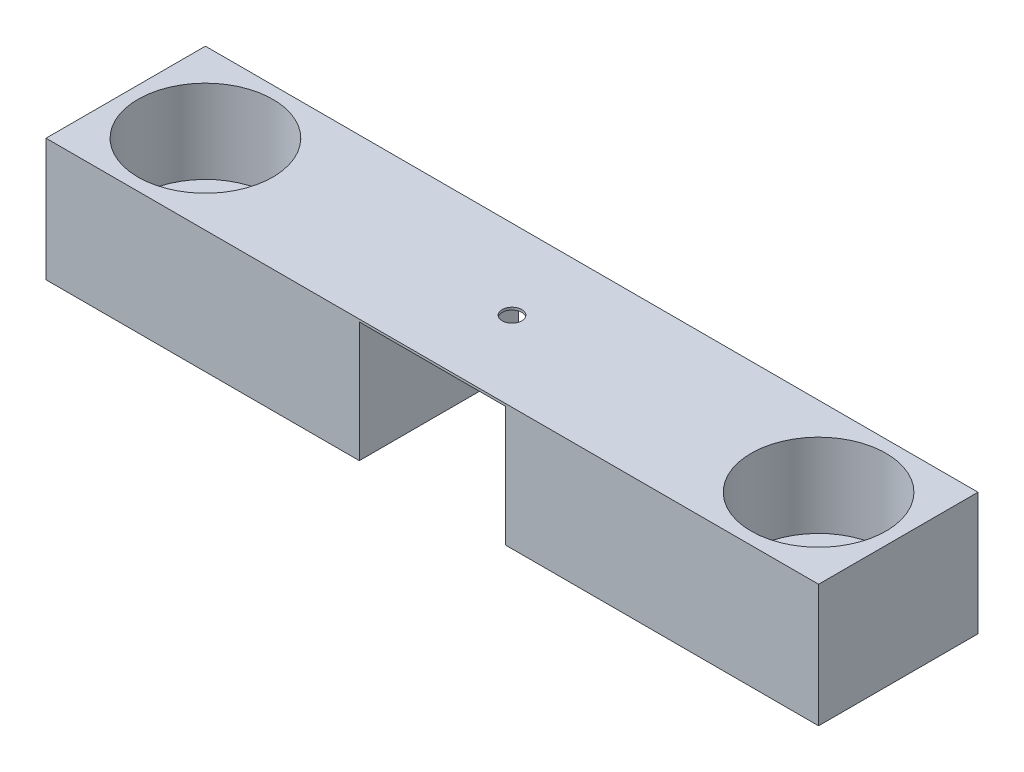
SolidWorks part; units mm, degrees
material "6061 合金"
ref_plane "前视基准面" through (0, 0, 0) normal (0, 0, 1) x (1, 0, 0)
ref_plane "上视基准面" through (0, 0, 0) normal (0, 1, 0) x (1, 0, 0)
ref_plane "右视基准面" through (0, 0, 0) normal (1, 0, 0) x (0, 0, -1)
sketch "草图1" plane through (0, 0, 0) normal (0, 1, 0) x (1, 0, 0)
  line L1 (-31.5, 6.5) -> (31.5, 6.5)
  line L2 (-31.5, 6.5) -> (-31.5, -6.5)
  line L3 (-31.5, -6.5) -> (31.5, -6.5)
  line L4 (31.5, 6.5) -> (31.5, -6.5)
  line L5 (-31.5, 6.5) -> (31.5, -6.5) construction
  line L6 (-31.5, -6.5) -> (31.5, 6.5) construction
  point P0 (0, 0)
extrude "凸台-拉伸1" add sketch "草图1" along normal blind 10
sketch "草图2" plane through (0, 10, 0) normal (0, 1, 0) x (1, 0, 0)
  line L0 (-25, 0) -> (25, 0) construction
  line L1 (-16.5, 0) -> (16.5, 0) construction
  point P6 (0, 0)
hole_wizard "打孔尺寸(%根据)内六角圆柱头螺钉的类型1" positions "3D草图1" profile "草图3" counterbore size "M6" standard "GB" end condition through all
sketch3d "3D草图1"
  point P0 (-25, 10, 0)
  point P3 (25, 10, 0)
sketch "草图3" plane through (-25, 10, 0) normal (1, 0, 0) x (0, 0, 1)
  line L0 (0, 0) -> (0, 10)
  line L1 (0, 10) -> (3.3, 10)
  line L3 (3.3, 10) -> (3.3, 6.8)
  line L4 (3.3, 6.8) -> (5.5, 6.8)
  line L5 (5.5, 6.8) -> (5.5, 0)
  line L7 (5.5, 0) -> (0, 0)
  line L11 (0, -6.35) -> (0, 107.95) construction
  dimension "通孔孔直径" = 6.6
  dimension "通孔孔深度" = 10
  dimension "柱形沉头孔直径" = 11
  dimension "柱形沉头孔深度" = 6.8
sketch "草图4" plane through (0, 0, 0) normal (0, -1, 0) x (1, 0, 0)
  line L0 (-25, 0) -> (-15, 0) construction
  line L1 (-25, 0) -> (25, 0) construction
  line L2 (25, 0) -> (15, 0) construction
  dimension "D1" = 10
  dimension "D2" = 10
hole_wizard "大小mm 暗销孔1" positions "3D草图2" profile "草图5" hole size "Ø4.0" standard "GB"
sketch3d "3D草图2"
  point P0 (-15, 0, 0)
sketch "草图5" plane through (-15, 0, 0) normal (1, 0, 0) x (0, 0, -1)
  line L0 (0, 0) -> (0, 6.2017)
  line L1 (0, 6.2017) -> (2, 5)
  line L2 (2, 5) -> (2, 0)
  line L5 (2, 0) -> (0, 0)
  line L10 (0, 6.2017) -> (-2, 5) construction
  line L11 (0, -6.35) -> (0, 107.95) construction
  dimension "孔直径" = 4
  dimension "孔深度" = 5
  dimension "导头角度" = 118
sketch "草图6" plane through (0, 0, 0) normal (0, -1, 0) x (1, 0, 0)
  line L0 (14.5, 0) -> (15.5, 0) construction
  line L1 (-25, 0) -> (25, 0) construction
  line L2 (14.5, 2) -> (15.5, 2)
  line L3 (14.5, -2) -> (15.5, -2)
  arc A0 (14.5, 2) -> (14.5, -2) centre (14.5, 0) ccw
  arc A1 (15.5, -2) -> (15.5, 2) centre (15.5, 0) ccw
  circle A2 centre (-15, 0) radius 2 construction
  point P5 (15, 0)
  dimension "D1" = 1
extrude "切除-拉伸1" cut sketch "草图6" against normal blind 5
fillet "圆角1" [suppressed] radius 2
sketch "草图7" plane through (0, 10, 0) normal (0, 1, 0) x (1, 0, 0)
  circle A0 centre (0, 0) radius 2
hole_wizard "M2 螺纹孔1" positions "3D草图3" profile "草图8" tap size "M2" standard "GB" end condition through all
sketch3d "3D草图3"
  line L0 (-25, 10, 0) -> (25, 10, 0) construction
  point P0 (0, 10, 0)
  point P4 (0, 10, 0)
  point P6 (0, 10, 0)
cosmetic thread "孔螺蚊线3" parameters "D2"=2
sketch "草图8" plane through (0, 10, 0) normal (1, 0, 0) x (0, 0, 1)
  line L0 (0, 0) -> (0, 10)
  line L1 (0, 10) -> (0.8, 10)
  line L2 (0.8, 10) -> (0.8, 0)
  line L5 (0.8, 0) -> (0, 0)
  line L11 (0, -6.35) -> (0, 107.95) construction
  dimension "通孔螺纹孔钻头直径" = 1.6
  dimension "通孔螺纹孔钻头深度" = 10
cosmetic thread "孔螺蚊线4" parameters "D2"=2
cosmetic thread "孔螺蚊线5" parameters "D2"=2
sketch "草图9" plane through (0, 0, 6.5) normal (0, 0, 1) x (1, 0, 0)
  line L0 (7.15, 0) -> (-7.15, 0) construction
  line L1 (-5.95, 9.8) -> (5.95, 9.8)
  line L2 (-5.95, 9.8) -> (-5.95, 0)
  line L3 (-5.95, 0) -> (5.95, 0)
  line L4 (5.95, 9.8) -> (5.95, 0)
  dimension "D1" = 9.8
  dimension "D2" = 5.95
  dimension "D3" = 11.9
extrude "切除-拉伸2" cut sketch "草图9" against normal through all
sketch "草图10" [suppressed] plane through (0, 0, 0) normal (0, -1, 0) x (-1, 0, 0)
  line L0 (15, 0) -> (15, -4) construction
  line L1 (15, -4) -> (17, -4) construction
  line L2 (-15, 0) -> (-15, 4) construction
  line L3 (-15, 4) -> (-17, 4) construction
  circle A0 centre (17, -4) radius 1.5009
  circle A1 centre (-17, 4) radius 1.5328
  dimension "D1" = 4
  dimension "D2" = 2
hole_wizard "大小mm 暗销孔2" [suppressed] positions "3D草图4" profile "草图11" hole size "Ø4.0" standard "GB"
sketch3d "3D草图4" [suppressed]
  point P0 (-17, 0, 4)
sketch "草图11" plane through (-17, 0, 4) normal (1, 0, 0) x (0, 0, -1)
  line L0 (0, 0) -> (0, 6.2017)
  line L1 (0, 6.2017) -> (2, 5)
  line L2 (2, 5) -> (2, 0)
  line L5 (2, 0) -> (0, 0)
  line L10 (0, 6.2017) -> (-2, 5) construction
  line L11 (0, -6.35) -> (0, 107.95) construction
  dimension "孔直径" = 4
  dimension "孔深度" = 5
  dimension "导头角度" = 118
sketch "草图12" [suppressed] plane through (0, 0, 0) normal (0, -1, 0) x (1, 0, 0)
  line L0 (17.5, -4) -> (16.5, -4) construction
  line L4 (15, -4) -> (17, -4) construction
  line L5 (17.5, -6) -> (16.5, -6)
  line L6 (17.5, -2) -> (16.5, -2)
  arc A2 (17.5, -6) -> (17.5, -2) centre (17.5, -4) ccw
  arc A3 (16.5, -2) -> (16.5, -6) centre (16.5, -4) ccw
  circle A4 centre (-15, 0) radius 2 construction
  point P5 (17, -4)
  dimension "D1" = 1
extrude "切除-拉伸3" [suppressed] cut sketch "草图12" against normal blind 5
